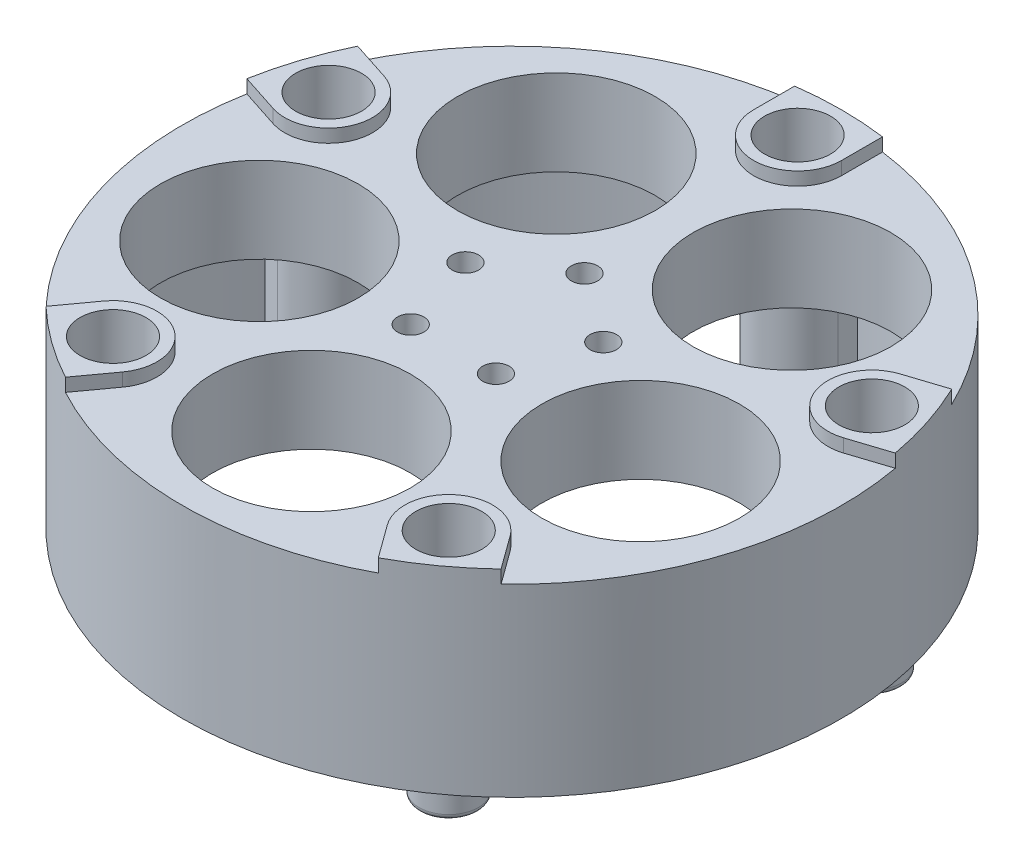
SolidWorks part; units mm, degrees
ref_plane "Front Plane" through (0, 0, 0) normal (0, 0, 1) x (1, 0, 0)
ref_plane "Top Plane" through (0, 0, 0) normal (0, 1, 0) x (1, 0, 0)
ref_plane "Right Plane" through (0, 0, 0) normal (1, 0, 0) x (0, 0, -1)
sketch "Sketch1" plane through (0, 0, 0) normal (0, 1, 0) x (1, 0, 0)
  circle A0 centre (0, 0) radius 30
extrude "Boss-Extrude1" add sketch "Sketch1" along normal blind 18 contours A0
sketch "Sketch2" plane through (0, 18, 0) normal (0, 1, 0) x (1, 0, 0)
  line L0 (-4, 26) -> (-4, 29.7321)
  line L1 (4, 26) -> (4, 29.7321)
  line L2 (23.4914, 11.8387) -> (27.0409, 12.992)
  line L3 (25.9635, 4.2302) -> (29.513, 5.3835)
  line L4 (18.5185, -18.6833) -> (20.7122, -21.7027)
  line L5 (12.0463, -23.3856) -> (14.24, -26.4049)
  line L6 (-12.0463, -23.3856) -> (-14.24, -26.4049)
  line L7 (-18.5185, -18.6833) -> (-20.7122, -21.7027)
  line L8 (-25.9635, 4.2302) -> (-29.513, 5.3835)
  line L9 (-23.4914, 11.8387) -> (-27.0409, 12.992)
  circle A0 centre (0, 26) radius 3 construction
  arc A5 (4, 29.7321) -> (-4, 29.7321) centre (0, 0) ccw
  arc A6 (-4, 26) -> (4, 26) centre (0, 26) ccw
  arc A7 (29.513, 5.3835) -> (27.0409, 12.992) centre (0, 0) ccw
  arc A8 (23.4914, 11.8387) -> (25.9635, 4.2302) centre (24.7275, 8.0344) ccw
  circle A9 centre (24.7275, 8.0344) radius 3 construction
  arc A10 (14.24, -26.4049) -> (20.7122, -21.7027) centre (0, 0) ccw
  arc A11 (18.5185, -18.6833) -> (12.0463, -23.3856) centre (15.2824, -21.0344) ccw
  circle A12 centre (15.2824, -21.0344) radius 3 construction
  arc A13 (-20.7122, -21.7027) -> (-14.24, -26.4049) centre (0, 0) ccw
  arc A14 (-12.0463, -23.3856) -> (-18.5185, -18.6833) centre (-15.2824, -21.0344) ccw
  circle A15 centre (-15.2824, -21.0344) radius 3 construction
  arc A16 (-27.0409, 12.992) -> (-29.513, 5.3835) centre (0, 0) ccw
  arc A17 (-25.9635, 4.2302) -> (-23.4914, 11.8387) centre (-24.7275, 8.0344) ccw
  circle A18 centre (-24.7275, 8.0344) radius 3 construction
  circle A19 centre (0, 0) radius 37.7826
  point P34 (0, 0)
  dimension "D1" = 5
extrude "Cut-Extrude1" cut sketch "Sketch2" against normal blind 1.2
sketch "Sketch3" plane through (0, 18, 0) normal (0, 1, 0) x (1, 0, 0)
  circle A1 centre (0, 26) radius 3
  circle A2 centre (24.7275, 8.0344) radius 3
  circle A3 centre (15.2824, -21.0344) radius 3
  circle A4 centre (-15.2824, -21.0344) radius 3
  circle A5 centre (-24.7275, 8.0344) radius 3
  point P13 (0, 0)
  dimension "D1" = 5
extrude "Cut-Extrude2" cut sketch "Sketch3" against normal blind 9.6
sketch "Sketch5" plane through (0, 0, 0) normal (0, -1, 0) x (1, 0, 0)
  line L0 (3.7, -26) -> (3.7, -27.7545)
  line L1 (-3.7, -26) -> (-3.7, -27.7545)
  line L2 (-23.5841, -11.5534) -> (-25.2527, -12.0955)
  line L3 (-25.8708, -4.5155) -> (-27.5394, -5.0577)
  line L4 (-18.2758, 18.8596) -> (-19.307, 20.279)
  line L5 (-12.2891, 23.2092) -> (-13.3203, 24.6286)
  line L6 (12.2891, 23.2092) -> (13.3203, 24.6286)
  line L7 (18.2758, 18.8596) -> (19.307, 20.279)
  line L8 (25.8708, -4.5155) -> (27.5394, -5.0577)
  line L9 (23.5841, -11.5534) -> (25.2527, -12.0955)
  arc A0 (27.5394, -5.0577) -> (19.307, 20.279) centre (0, 0) ccw
  circle A1 centre (0, 0) radius 22.3 construction
  arc A2 (3.7, -26) -> (-3.7, -26) centre (0, -26) ccw
  arc A3 (-23.5841, -11.5534) -> (-25.8708, -4.5155) centre (-24.7275, -8.0344) ccw
  arc A4 (-18.2758, 18.8596) -> (-12.2891, 23.2092) centre (-15.2824, 21.0344) ccw
  arc A5 (12.2891, 23.2092) -> (18.2758, 18.8596) centre (15.2824, 21.0344) ccw
  arc A6 (25.8708, -4.5155) -> (23.5841, -11.5534) centre (24.7275, -8.0344) ccw
  arc A7 (3.7, -27.7545) -> (25.2527, -12.0955) centre (0, 0) ccw
  arc A8 (-25.2527, -12.0955) -> (-3.7, -27.7545) centre (0, 0) ccw
  arc A9 (-19.307, 20.279) -> (-27.5394, -5.0577) centre (0, 0) ccw
  arc A10 (13.3203, 24.6286) -> (-13.3203, 24.6286) centre (0, 0) ccw
  point P27 (0, 0)
extrude "Cut-Extrude4" cut sketch "Sketch5" against normal blind 9
sketch "Sketch6" plane through (0, 9, 0) normal (0, -1, 0) x (1, 0, 0)
  line L0 (0, 27.25) -> (0, 18.25) construction
  line L1 (0, 0) -> (15.2824, 21.0344) construction
  circle A0 centre (0, 0) radius 18.25 construction
  circle A1 centre (0, 18.25) radius 9
  circle A2 centre (0, 0) radius 27.25 construction
  circle A3 centre (17.3568, 5.6396) radius 9
  circle A4 centre (10.7271, -14.7646) radius 9
  circle A5 centre (-10.7271, -14.7646) radius 9
  circle A6 centre (-17.3568, 5.6396) radius 9
  circle A7 centre (0, 0) radius 7.8 construction
  circle A8 centre (0, 0) radius 6.6 construction
  circle A9 centre (3.8794, 5.3395) radius 1.2
  circle A10 centre (6.277, -2.0395) radius 1.2
  circle A11 centre (0, -6.6) radius 1.2
  circle A12 centre (-6.277, -2.0395) radius 1.2
  circle A13 centre (-3.8794, 5.3395) radius 1.2
  point P18 (0, 0)
  point P32 (0, 0)
  dimension "D1" = 5
  dimension "D2" = 5
extrude "Cut-Extrude5" cut sketch "Sketch6" against normal through all
sketch "Sketch7" plane through (0, 9, 0) normal (0, -1, 0) x (1, 0, 0)
  circle A3 centre (-3.8794, 5.3395) radius 1.2
  circle A4 centre (-3.8794, 5.3395) radius 1.2
  circle A13 centre (3.8794, 5.3395) radius 1.2
  circle A14 centre (3.8794, 5.3395) radius 1.2
  circle A15 centre (6.277, -2.0395) radius 1.2
  circle A16 centre (6.277, -2.0395) radius 1.2
  circle A17 centre (0, -6.6) radius 1.2
  circle A18 centre (0, -6.6) radius 1.2
  circle A19 centre (-6.277, -2.0395) radius 1.2
  circle A20 centre (-6.277, -2.0395) radius 1.2
  arc A21 (-2.9353, 8.4815) -> (2.9353, 8.4815) centre (0, 18.25) ccw
  arc A22 (7.1593, 5.4125) -> (8.9734, -0.1707) centre (17.3568, 5.6396) ccw
  arc A23 (7.36, -5.1363) -> (2.6106, -8.587) centre (10.7271, -14.7646) ccw
  arc A24 (-2.6106, -8.587) -> (-7.36, -5.1363) centre (-10.7271, -14.7646) ccw
  arc A25 (-8.9734, -0.1707) -> (-7.1593, 5.4125) centre (-17.3568, 5.6396) ccw
  arc A26 (-2.9353, 8.4815) -> (-7.1593, 5.4125) centre (-3.8794, 5.3395) ccw
  arc A27 (7.1593, 5.4125) -> (2.9353, 8.4815) centre (3.8794, 5.3395) ccw
  arc A28 (7.36, -5.1363) -> (8.9734, -0.1707) centre (6.277, -2.0395) ccw
  arc A29 (-2.6106, -8.587) -> (2.6106, -8.587) centre (0, -6.6) ccw
  arc A30 (-8.9734, -0.1707) -> (-7.36, -5.1363) centre (-6.277, -2.0395) ccw
  dimension "D2" = 0
  dimension "D7" = 0
  dimension "D8" = 0
  dimension "D9" = 0
  dimension "D10" = 0
extrude "Cut-Extrude6" cut sketch "Sketch7" against normal blind 1.8
sketch "Sketch8" plane through (0, 0, 0) normal (0, -1, 0) x (1, 0, 0)
  circle A0 centre (0, -26) radius 2.7
  circle A1 centre (-24.7275, -8.0344) radius 2.7
  circle A2 centre (-15.2824, 21.0344) radius 2.7
  circle A3 centre (15.2824, 21.0344) radius 2.7
  circle A4 centre (24.7275, -8.0344) radius 2.7
  point P13 (0, 0)
  dimension "D1" = 5
extrude "Boss-Extrude2" add sketch "Sketch8" along normal blind 3
sketch "Sketch4" plane through (0, 8.4, 0) normal (0, 1, 0) x (1, 0, 0)
  circle A0 centre (0, 26) radius 1.6
  circle A1 centre (24.7275, 8.0344) radius 1.6
  circle A2 centre (15.2824, -21.0344) radius 1.6
  circle A3 centre (-15.2824, -21.0344) radius 1.6
  circle A4 centre (-24.7275, 8.0344) radius 1.6
  point P13 (0, 0)
  dimension "D1" = 5
extrude "Cut-Extrude7" cut sketch "Sketch4" against normal through all
fillet "Fillet1" radius 0.5 5 edges at (0, -3, -28.7) (24.7275, -3, -10.7344) (15.2824, -3, 18.3344) (-15.2824, -3, 18.3344) (-24.7275, -3, -10.7344)
